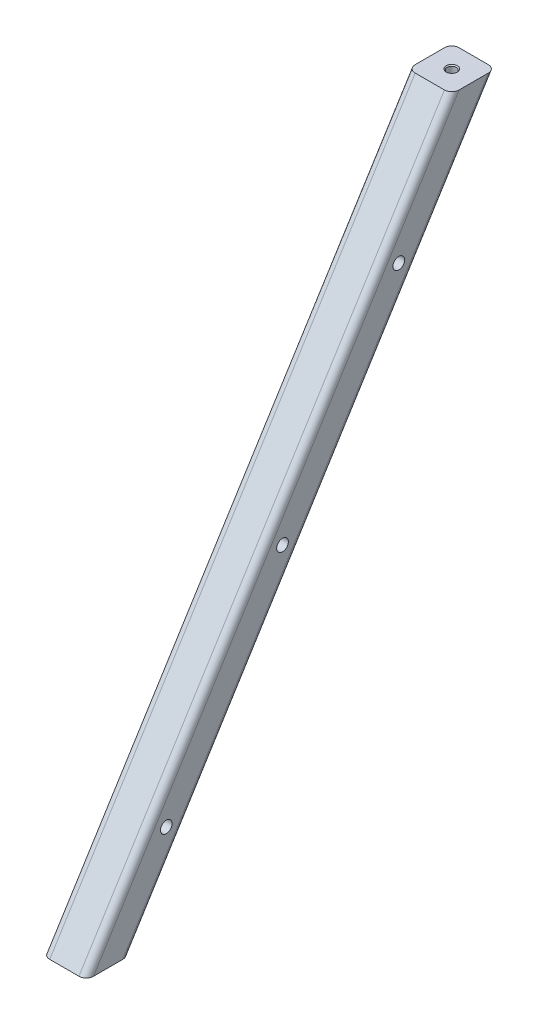
SolidWorks part; units mm, degrees
ref_plane "前视基准面" through (0, 0, 0) normal (0, 0, 1) x (1, 0, 0)
ref_plane "上视基准面" through (0, 0, 0) normal (0, 1, 0) x (1, 0, 0)
ref_plane "右视基准面" through (0, 0, 0) normal (1, 0, 0) x (0, 0, -1)
other "Configuration Table"
sketch "草图1" plane through (0, 0, 0) normal (0, 1, 0) x (1, 0, 0)
  line L1 (-4, 6) -> (4, 6)
  line L2 (-6, 4) -> (-6, -4)
  line L3 (-4, -6) -> (4, -6)
  line L4 (6, 4) -> (6, -4)
  line L5 (-6, 6) -> (6, -6) construction
  line L6 (-6, -6) -> (6, 6) construction
  arc A0 (4, 6) -> (6, 4) centre (4, 4) cw
  arc A1 (4, -6) -> (6, -4) centre (4, -4) ccw
  arc A2 (-6, -4) -> (-4, -6) centre (-4, -4) ccw
  arc A3 (-4, 6) -> (-6, 4) centre (-4, 4) ccw
  point P0 (0, 0)
  dimension "D3" = 2
  dimension "D1" = 12
  dimension "D2" = 12
ref_plane "基准面1" through (0, 0, 0) normal (1, 0, 0) x (0, 0, -1)
sketch "草图2" plane through (0, 0, 0) normal (1, 0, 0) x (0, 0, -1)
  line L0 (0, 0) -> (100, 160)
  line L1 (100, 160) -> (0, 160) construction
  line L2 (0, 160) -> (0, 0) construction
  dimension "D1" = 160
  dimension "D2" = 100
sweep "扫描2" add profiles "草图1" path "草图2"
sketch "草图3" plane through (0, 0, 0) normal (0, -1, 0) x (1, 0, 0)
  circle A0 centre (0, 0) radius 1.5
  point P0 (0, 0)
  dimension "D1" = 3
hole_wizard "M3 螺纹孔1" positions "草图3" profile "草图4" tap size "M3" standard "GB"
sketch "草图4" plane through (0, 0, 0) normal (1, 0, 0) x (0, 0, -1)
  line L0 (0, 0) -> (0, 6)
  line L1 (0, 6) -> (1.25, 5.2489)
  line L2 (1.25, 5.2489) -> (1.25, 0.275)
  line L3 (1.25, 0.275) -> (1.525, 0)
  line L5 (1.525, 0) -> (0, 0)
  line L6 (-1.25, 0.275) -> (-1.525, 0) construction
  line L10 (0, 6) -> (-1.25, 5.2489) construction
  line L11 (0, -6.35) -> (0, 107.95) construction
  dimension "螺纹孔钻头直径" = 2.5
  dimension "螺纹孔钻头深度" = 6
  dimension "近端锥形沉头孔直径" = 3.05
  dimension "近端锥形沉头孔角度" = 90
  dimension "导头角度" = 118
cosmetic thread "孔螺蚊线1" parameters "D1"=6, "D2"=3
sketch "草图5" plane through (0, 160, 0) normal (0, 1, 0) x (1, 0, 0)
  line L0 (-4, 104) -> (4, 96) construction
  line L1 (-4, 96) -> (4, 104) construction
  circle A0 centre (0, 100) radius 1.5
  point P4 (0, 100)
  dimension "D1" = 3
hole_wizard "M3 螺纹孔2" positions "草图5" profile "草图6" tap size "M3" standard "GB"
sketch "草图6" plane through (0, 160, -100) normal (1, 0, 0) x (0, 0, 1)
  line L0 (0, 0) -> (0, 6)
  line L1 (0, 6) -> (1.25, 5.2489)
  line L2 (1.25, 5.2489) -> (1.25, 0.275)
  line L3 (1.25, 0.275) -> (1.525, 0)
  line L5 (1.525, 0) -> (0, 0)
  line L6 (-1.25, 0.275) -> (-1.525, 0) construction
  line L10 (0, 6) -> (-1.25, 5.2489) construction
  line L11 (0, -6.35) -> (0, 107.95) construction
  dimension "螺纹孔钻头直径" = 2.5
  dimension "螺纹孔钻头深度" = 6
  dimension "近端锥形沉头孔直径" = 3.05
  dimension "近端锥形沉头孔角度" = 90
  dimension "导头角度" = 118
cosmetic thread "孔螺蚊线2" parameters "D1"=6, "D2"=3
sketch "草图7" plane through (6, 0, 0) normal (1, 0, 0) x (0, 0, -1)
  line L0 (0, 0) -> (100, 160) construction
  line L1 (-4, 0) -> (4, 0) construction
  line L2 (96, 160) -> (104, 160) construction
  circle A0 centre (15.9, 25.4399) radius 1.6
  circle A1 centre (47.6999, 76.3198) radius 1.6
  circle A2 centre (79.4998, 127.1997) radius 1.6
  dimension "D1" = 3.2
  dimension "D2" = 30
  dimension "D3" = 3
extrude "切除-拉伸1" cut sketch "草图7" against normal up to next
